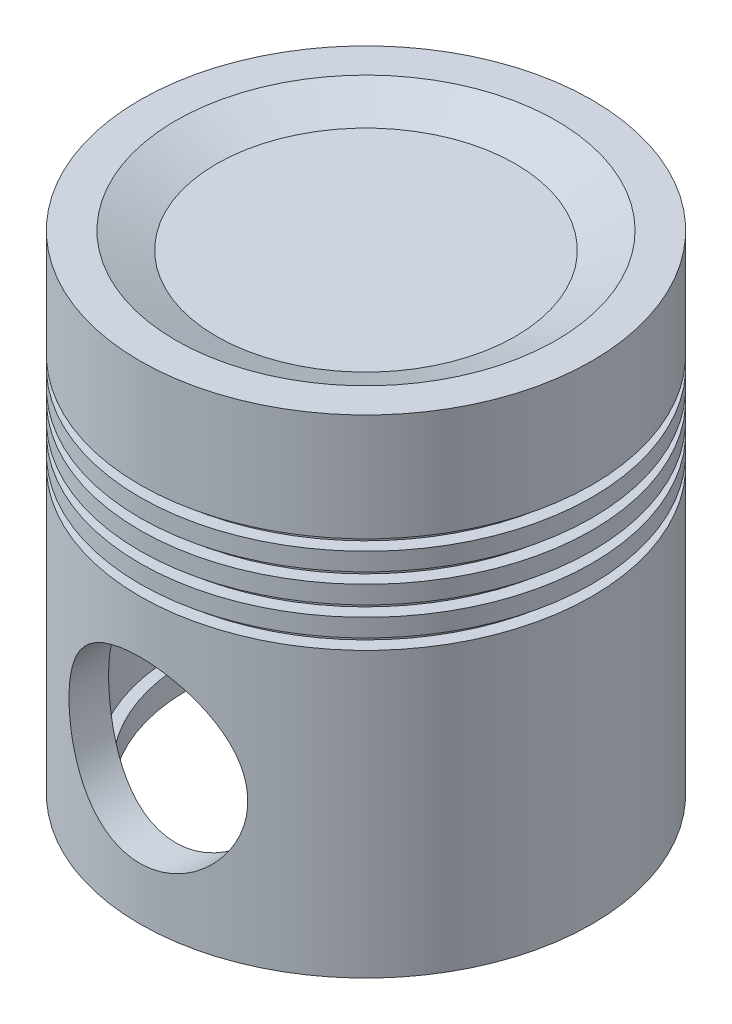
SolidWorks part; units mm, degrees
material "2618-T61 (SS)"
ref_plane "Front Plane" through (0, 0, 0) normal (0, 0, 1) x (1, 0, 0)
ref_plane "Top Plane" through (0, 0, 0) normal (0, 1, 0) x (1, 0, 0)
ref_plane "Right Plane" through (0, 0, 0) normal (1, 0, 0) x (0, 0, -1)
sketch "Sketch1" plane through (0, 0, 0) normal (0, 0, 1) x (1, 0, 0)
  line L0 (0, 112.6935) -> (0, -113.5879) construction
  line L2 (-63.2037, 71.6167) -> (-63.2037, 41.6167)
  line L3 (-63.2037, 41.6167) -> (-59.6262, 41.6167)
  line L4 (-59.6262, 41.6167) -> (-59.6262, 38.6167)
  line L5 (-59.6262, 38.6167) -> (-63.2037, 38.6167)
  line L6 (-63.2037, 38.6167) -> (-63.2037, 33.6167)
  line L7 (-63.2037, 33.6167) -> (-59.6262, 33.6167)
  line L8 (-59.6262, 33.6167) -> (-59.6262, 30.6167)
  line L9 (-59.6262, 30.6167) -> (-63.2037, 30.6167)
  line L10 (-63.2037, 30.6167) -> (-63.2037, 25.6167)
  line L11 (-59.6262, 25.6167) -> (-63.2037, 25.6167)
  line L12 (-59.6262, 25.6167) -> (-59.6262, 22.6167)
  line L13 (-59.6262, 22.6167) -> (-63.2037, 22.6167)
  line L14 (-63.2037, 22.6167) -> (-63.2037, 17.6167)
  line L15 (-63.2037, 17.6167) -> (-59.6262, 17.6167)
  line L16 (-59.6262, 17.6167) -> (-59.6262, 14.6167)
  line L17 (-59.6262, 14.6167) -> (-63.2037, 14.6167)
  line L18 (-63.2037, 14.6167) -> (-63.2037, -64.7409)
  line L19 (-63.2037, -64.7409) -> (0, -64.7409)
  line L20 (0, -64.7409) -> (0, -57.7409)
  line L21 (0, -57.7409) -> (-53.2037, -57.7409)
  line L22 (-53.2037, -57.7409) -> (-53.2037, 56.6167)
  line L23 (0, 56.6167) -> (-53.2037, 56.6167)
  line L26 (0, 66.8524) -> (0, 56.6167)
  line L27 (-63.2037, 71.6167) -> (-53.2037, 71.6167)
  line L29 (-53.2037, 71.6167) -> (-41.7896, 66.8524)
  line L30 (-41.7896, 66.8524) -> (0, 66.8524)
  dimension "D1" = 3
  dimension "D2" = 5
  dimension "D3" = 10
  dimension "D5" = 30
  dimension "D6" = 7
revolve "Revolve1" add sketch "Sketch1" angle 360 about L0
sketch "Sketch2" plane through (0, 0, 0) normal (0, 0, 1) x (1, 0, 0)
  line L0 (0, 74.6895) -> (0, -69.8601) construction
  line L1 (-63.2037, -25.0621) -> (57.299, -25.0621) construction
  line L2 (-63.2037, 14.6167) -> (-63.2037, -64.7409) construction
  circle A0 centre (0, -25.0621) radius 25
  dimension "D1" = 50
extrude "Cut-Extrude2" cut sketch "Sketch2" against normal through all both and the other way through all
sketch "Sketch3" plane through (0, -64.7409, 0) normal (0, -1, 0) x (1, 0, 0)
  circle A0 centre (0, 0) radius 50
  dimension "D1" = 100
extrude "Cut-Extrude4" cut sketch "Sketch3" against normal blind 11
